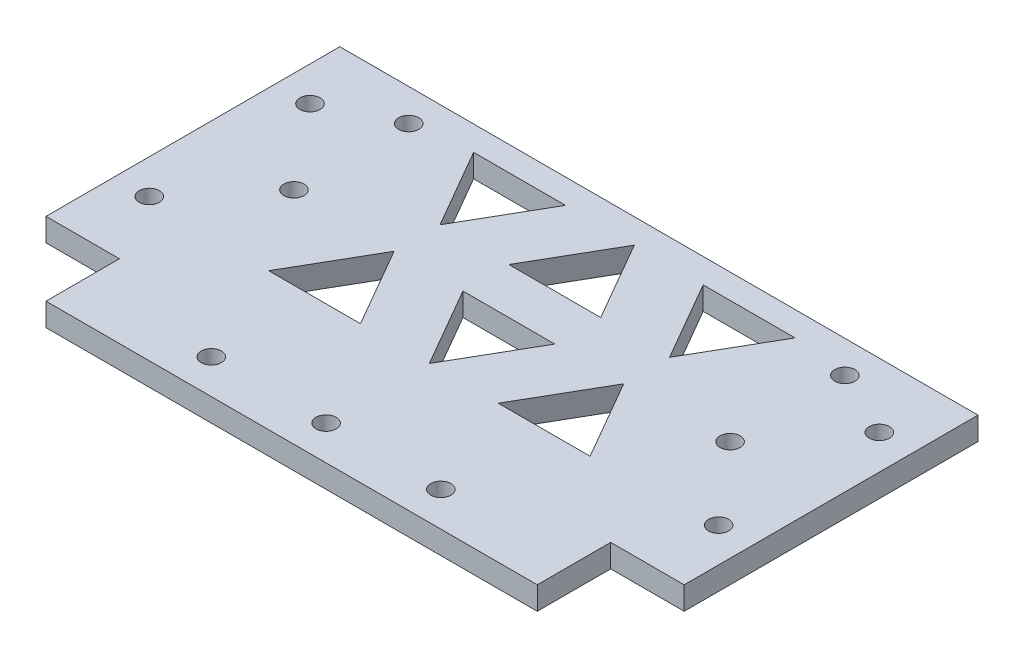
SolidWorks part; units mm, degrees
other "Markup1"
sketch "Sketch7" plane through (-69.5, 3, -80) normal (0, 1, 0) x (1, 0, 0)
sketch "Sketch8" plane through (-69.5, 5, -80) normal (0, 1, 0) x (1, 0, 0)
ref_plane "Front Plane" through (0, 0, 0) normal (0, 0, 1) x (1, 0, 0)
ref_plane "Top Plane" through (0, 0, 0) normal (0, 1, 0) x (1, 0, 0)
ref_plane "Right Plane" through (0, 0, 0) normal (1, 0, 0) x (0, 0, -1)
sketch "Sketch1" plane through (0, 0, 0) normal (0, 1, 0) x (1, 0, 0)
  line L1 (-69.5, 80) -> (69.5, 80)
  line L2 (-69.5, 80) -> (-69.5, -80)
  line L3 (-69.5, -80) -> (69.5, -80)
  line L4 (69.5, 80) -> (69.5, -80)
  line L5 (-69.5, 80) -> (69.5, -80) construction
  line L6 (-69.5, -80) -> (69.5, 80) construction
  point P0 (0, 0)
  dimension "D1" = 160
  dimension "D2" = 139
extrude "Boss-Extrude1" add sketch "Sketch1" along normal blind 5
sketch "Sketch2" plane through (0, 5, 0) normal (0, 1, 0) x (1, 0, 0)
  line L1 (-69.5, -80) -> (-53.5, -80)
  line L2 (-69.5, -80) -> (-69.5, -64)
  line L3 (-69.5, -64) -> (-53.5, -64)
  line L4 (-53.5, -80) -> (-53.5, -64)
  dimension "D1" = 16
  dimension "D2" = 16
extrude "Cut-Extrude1" cut sketch "Sketch2" against normal through all
mirror "Mirror1" about plane through (0, 0, 0) normal (1, 0, 0) of "Cut-Extrude1"
sketch "Sketch3" plane through (0, 5, 0) normal (0, 1, 0) x (1, 0, 0)
  line L0 (0, -2.75) -> (0, 2.75) construction
  line L1 (-53.5, -80) -> (53.5, -80) construction
  circle A0 centre (0, -72.5) radius 2.2
  circle A1 centre (-25, -72.5) radius 2.2
  circle A2 centre (25, -72.5) radius 2.2
  dimension "D1" = 4.4
  dimension "D2" = 4.4
  dimension "D3" = 4.4
  dimension "D4" = 25
  dimension "D5" = 25
  dimension "D6" = 7.5
extrude "Cut-Extrude2" cut sketch "Sketch3" against normal through all
sketch "Sketch4" plane through (0, 5, 0) normal (0, 1, 0) x (1, 0, 0)
  line L0 (-53.5, -64) -> (-69.5, -64) construction
  line L1 (-69.5, 80) -> (-69.5, -64) construction
  circle A0 centre (-62, -49) radius 2.2
  dimension "D3" = 4.4
  dimension "D1" = 15
  dimension "D2" = 7.5
extrude "Cut-Extrude3" cut sketch "Sketch4" against normal through all
pattern_linear "LPattern1" count 4 spacing 35 along (0, 0, -1) of "Cut-Extrude3"
mirror "Mirror2" about plane through (0, 0, 0) normal (1, 0, 0) of "LPattern1", "Cut-Extrude3"
sketch "Sketch5" plane through (0, 5, 0) normal (0, 1, 0) x (1, 0, 0)
  line L0 (0, -2.75) -> (0, 2.75) construction
  line L1 (-53.5, -80) -> (53.5, -80) construction
  circle A0 centre (-47.5, -32) radius 2.2
  circle A1 centre (-47.5, -7) radius 2.2
  dimension "D4" = 4.4
  dimension "D5" = 4.4
  dimension "D1" = 47.5
  dimension "D2" = 47.5
  dimension "D3" = 25
  dimension "D6" = 48
extrude "Cut-Extrude4" cut sketch "Sketch5" against normal through all
mirror "Mirror3" about plane through (0, 0, 0) normal (1, 0, 0) of "Cut-Extrude4"
sketch "Sketch6" plane through (0, 5, 0) normal (0, 1, 0) x (1, 0, 0)
  line L0 (0, 50) -> (-10, 32.6795)
  line L3 (0, -2.75) -> (0, 2.75) construction
  line L8 (-10, 32.6795) -> (10, 32.6795)
  line L9 (10, 32.6795) -> (0, 50)
  line L10 (69.5, 80) -> (-69.5, 80) construction
  line L11 (15, 50) -> (25, 32.6795)
  line L12 (25, 32.6795) -> (35, 50)
  line L13 (35, 50) -> (15, 50)
  line L15 (-25, 32.6795) -> (-35, 50)
  line L16 (-15, 50) -> (-25, 32.6795)
  line L17 (-35, 50) -> (-15, 50)
  line L18 (0, 27.6795) -> (-71.171, 27.6795) construction
  line L19 (25, 22.6795) -> (35, 5.359)
  line L20 (15, 5.359) -> (25, 22.6795)
  line L21 (35, 5.359) -> (15, 5.359)
  line L22 (-10, 22.6795) -> (10, 22.6795)
  line L23 (0, 5.359) -> (-10, 22.6795)
  line L24 (10, 22.6795) -> (0, 5.359)
  line L25 (-15, 5.359) -> (-25, 22.6795)
  line L26 (-35, 5.359) -> (-15, 5.359)
  line L27 (-25, 22.6795) -> (-35, 5.359)
  line L28 (-2.75, 0) -> (2.75, 0) construction
  line L29 (15, -5.359) -> (25, -22.6795)
  line L30 (35, -5.359) -> (15, -5.359)
  line L31 (25, -22.6795) -> (35, -5.359)
  line L32 (0, -5.359) -> (-10, -22.6795)
  line L33 (10, -22.6795) -> (0, -5.359)
  line L34 (-10, -22.6795) -> (10, -22.6795)
  line L35 (-35, -5.359) -> (-15, -5.359)
  line L36 (-25, -22.6795) -> (-35, -5.359)
  line L37 (-15, -5.359) -> (-25, -22.6795)
  line L38 (25, -32.6795) -> (35, -50)
  line L39 (15, -50) -> (25, -32.6795)
  line L40 (35, -50) -> (15, -50)
  line L41 (-10, -32.6795) -> (10, -32.6795)
  line L42 (0, -50) -> (-10, -32.6795)
  line L43 (10, -32.6795) -> (0, -50)
  line L44 (-15, -50) -> (-25, -32.6795)
  line L45 (-35, -50) -> (-15, -50)
  line L46 (-25, -32.6795) -> (-35, -50)
  point P0 (0, 32.6795)
  point P9 (0, 41.3108)
  dimension "D1" = 20
  dimension "D2" = 0
  dimension "D3" = 20
  dimension "D4" = 20
  dimension "D5" = 30
  dimension "D6" = 20
  dimension "D7" = 20
  dimension "D8" = 20
  dimension "D9" = 15
  dimension "D10" = 5
extrude "Cut-Extrude5" cut sketch "Sketch6" against normal through all
sketch "Sketch9" plane through (0, 5, 0) normal (0, 1, 0) x (1, 0, 0)
  line L6 (69.5, -64) -> (69.5, 80) construction
  line L7 (-69.5, 80) -> (69.5, 80)
  line L8 (-69.5, 80) -> (-69.5, 0)
  line L9 (-69.5, 0) -> (69.5, 0)
  line L10 (69.5, 80) -> (69.5, 0)
  dimension "D1" = 80
extrude "Cut-Extrude6" cut sketch "Sketch9" against normal blind 10
equation "\"D3@Sketch3\"=\"D1@Sketch3\""
equation "\"D2@Sketch3\"=\"D1@Sketch3\""
equation "\"D2@Sketch5\"=\"D1@Sketch5\""
